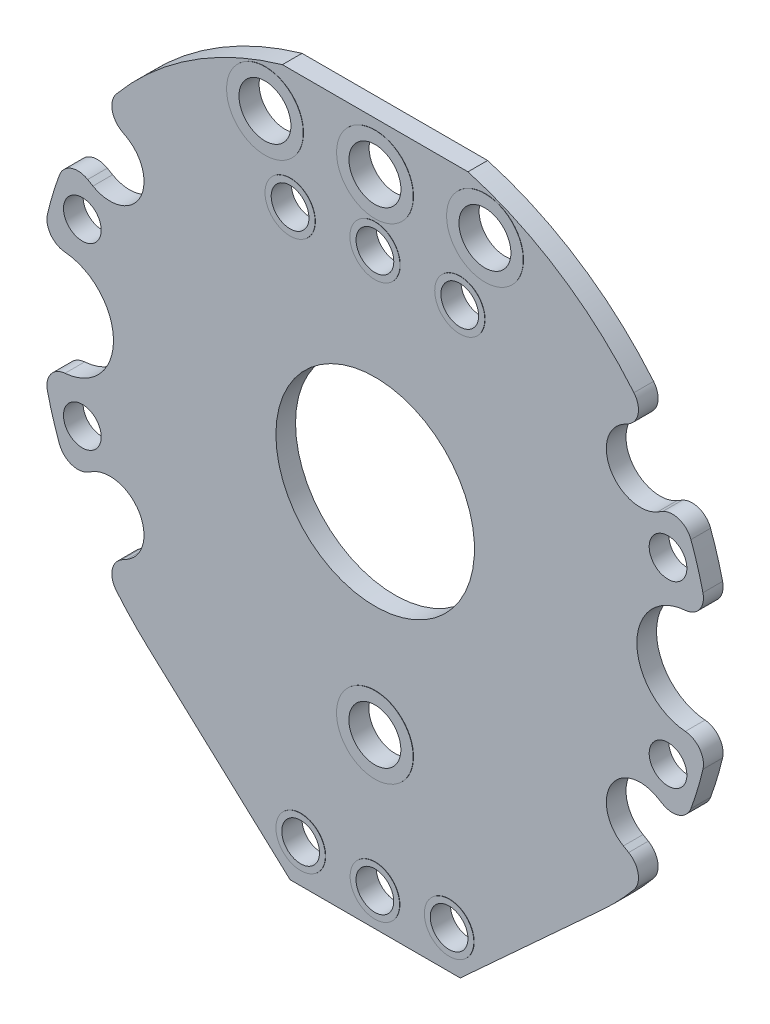
SolidWorks part; units mm, degrees
ref_plane "Front Plane" through (0, 0, 0) normal (0, 0, 1) x (1, 0, 0)
ref_plane "Top Plane" through (0, 0, 0) normal (0, 1, 0) x (1, 0, 0)
ref_plane "Right Plane" through (0, 0, 0) normal (1, 0, 0) x (0, 0, -1)
ref_plane "Plane4" through (0, 0, -0.7937) normal (0, 0, -1) x (-1, 0, 0)
sketch "Sketch1" plane through (0, 0, -0.7937) normal (0, 0, -1) x (-1, 0, 0)
  line L0 (-18.3768, -20.0548) -> (0, -36.8941)
  line L1 (0, -36.8941) -> (18.3768, -20.0548)
  line L2 (7.5, 26.1468) -> (-7.5, 26.1468)
  arc A0 (18.3768, -20.0548) -> (7.5, 26.1468) centre (0, 0) ccw
  arc A1 (-7.5, 26.1468) -> (-18.3768, -20.0548) centre (0, 0) ccw
  dimension "D1" = 15
  dimension "D2" = 26.1468
extrude "Boss-Extrude1" add sketch "Sketch1" against normal blind 1.5875
sketch "Sketch2" plane through (0, 0, 0.7937) normal (0, 0, 1) x (1, 0, 0)
  line L0 (-25.0713, 11.2995) -> (-22.8091, 9.9934)
  line L1 (-20.0591, 14.7566) -> (-22.3213, 16.0626)
  arc A0 (-22.3213, 16.0626) -> (-25.0713, 11.2995) centre (0, 0) ccw
  arc A1 (-22.8091, 9.9934) -> (-20.0591, 14.7566) centre (-21.4341, 12.375) ccw
extrude "Cut-Extrude1" cut sketch "Sketch2" against normal through all
sketch "Sketch3" plane through (0, 0, 0.7937) normal (0, 0, 1) x (1, 0, 0)
  line L0 (22.3213, 16.0626) -> (20.0591, 14.7566)
  line L1 (22.8091, 9.9934) -> (25.0713, 11.2995)
  arc A0 (25.0713, 11.2995) -> (22.3213, 16.0626) centre (0, 0) ccw
  arc A1 (20.0591, 14.7566) -> (22.8091, 9.9934) centre (21.4341, 12.375) ccw
extrude "Cut-Extrude2" cut sketch "Sketch3" against normal through all
sketch "Sketch4" plane through (0, 0, 0.7937) normal (0, 0, 1) x (1, 0, 0)
  line L0 (25.0713, -11.2995) -> (22.8091, -9.9934)
  line L1 (20.0591, -14.7566) -> (22.3213, -16.0626)
  arc A0 (22.3213, -16.0626) -> (25.0713, -11.2995) centre (0, 0) ccw
  arc A1 (22.8091, -9.9934) -> (20.0591, -14.7566) centre (21.4341, -12.375) ccw
extrude "Cut-Extrude3" cut sketch "Sketch4" against normal through all
sketch "Sketch5" plane through (0, 0, 0.7937) normal (0, 0, 1) x (1, 0, 0)
  line L0 (-22.3213, -16.0626) -> (-20.0591, -14.7566)
  line L1 (-22.8091, -9.9934) -> (-25.0713, -11.2995)
  arc A0 (-25.0713, -11.2995) -> (-22.3213, -16.0626) centre (0, 0) ccw
  arc A1 (-20.0591, -14.7566) -> (-22.8091, -9.9934) centre (-21.4341, -12.375) ccw
extrude "Cut-Extrude4" cut sketch "Sketch5" against normal through all
ref_plane "Plane5" through (0, -17, 0) normal (0, -1, 0) x (1, 0, 0)
sketch "Sketch6" plane through (0, -17, 0) normal (0, -1, 0) x (1, 0, 0)
  line L0 (3.0988, 0.8191) -> (0, 0.8192)
  line L1 (0, 0.8192) -> (0, 0.7937)
  line L2 (0, 0.7937) -> (3.0988, 0.7937)
  line L3 (3.0988, 0.7937) -> (3.0988, 0.8191)
  line L4 (0, 0.8192) -> (0, 0.7937) construction
revolve "Revolve1" add sketch "Sketch6" angle 360 about L4
ref_plane "Plane6" through (0, 17.78, 0) normal (0, -1, 0) x (1, 0, 0)
sketch "Sketch7" plane through (0, 17.78, 0) normal (0, -1, 0) x (1, 0, 0)
  line L0 (3.0988, 0.8191) -> (0, 0.8192)
  line L1 (0, 0.8192) -> (0, 0.7937)
  line L2 (0, 0.7937) -> (3.0988, 0.7937)
  line L3 (3.0988, 0.7937) -> (3.0988, 0.8191)
  line L4 (0, 0.8192) -> (0, 0.7937) construction
revolve "Revolve2" [suppressed] add sketch "Sketch7" angle 360 about L4
ref_plane "Plane7" through (0, -27.6013, 0) normal (0, -1, 0) x (1, 0, 0)
sketch "Sketch8" plane through (0, -27.6013, 0) normal (0, -1, 0) x (1, 0, 0)
  line L0 (-5.3958, 0.8191) -> (-7.3958, 0.8192)
  line L1 (-7.3958, 0.8192) -> (-7.3958, 0.7937)
  line L2 (-7.3958, 0.7937) -> (-5.3958, 0.7937)
  line L3 (-5.3958, 0.7937) -> (-5.3958, 0.8191)
  line L4 (-7.3958, 0.8192) -> (-7.3958, 0.7937) construction
revolve "Revolve3" [suppressed] add sketch "Sketch8" angle 360 about L4
sketch "Sketch9" plane through (0, -27.6013, 0) normal (0, -1, 0) x (1, 0, 0)
  line L0 (9.3958, 0.8191) -> (7.3958, 0.8192)
  line L1 (7.3958, 0.8192) -> (7.3958, 0.7937)
  line L2 (7.3958, 0.7937) -> (9.3958, 0.7937)
  line L3 (9.3958, 0.7937) -> (9.3958, 0.8191)
  line L4 (7.3958, 0.8192) -> (7.3958, 0.7937) construction
revolve "Revolve4" [suppressed] add sketch "Sketch9" angle 360 about L4
ref_plane "Plane8" through (0, -28.575, 0) normal (0, -1, 0) x (1, 0, 0)
sketch "Sketch10" plane through (0, -28.575, 0) normal (0, -1, 0) x (1, 0, 0)
  line L0 (2, 0.8191) -> (0, 0.8192)
  line L1 (0, 0.8192) -> (0, 0.7937)
  line L2 (0, 0.7937) -> (2, 0.7937)
  line L3 (2, 0.7937) -> (2, 0.8191)
  line L4 (0, 0.8192) -> (0, 0.7937) construction
revolve "Revolve5" add sketch "Sketch10" angle 360 about L4
ref_plane "Plane9" through (0, 16.4194, 0) normal (0, -1, 0) x (1, 0, 0)
sketch "Sketch11" plane through (0, 16.4194, 0) normal (0, -1, 0) x (1, 0, 0)
  line L0 (-3.7225, 0.8191) -> (-6.8213, 0.8192)
  line L1 (-6.8213, 0.8192) -> (-6.8213, 0.7937)
  line L2 (-6.8213, 0.7937) -> (-3.7225, 0.7937)
  line L3 (-3.7225, 0.7937) -> (-3.7225, 0.8191)
  line L4 (-6.8213, 0.8192) -> (-6.8213, 0.7937) construction
revolve "Revolve6" [suppressed] add sketch "Sketch11" angle 360 about L4
sketch "Sketch12" plane through (0, 16.4194, 0) normal (0, -1, 0) x (1, 0, 0)
  line L0 (9.9201, 0.8191) -> (6.8213, 0.8192)
  line L1 (6.8213, 0.8192) -> (6.8213, 0.7937)
  line L2 (6.8213, 0.7937) -> (9.9201, 0.7937)
  line L3 (9.9201, 0.7937) -> (9.9201, 0.8191)
  line L4 (6.8213, 0.8192) -> (6.8213, 0.7937) construction
revolve "Revolve7" [suppressed] add sketch "Sketch12" angle 360 about L4
sketch "Sketch15" plane through (0, -27.6013, 0) normal (0, -1, 0) x (1, 0, 0)
  line L0 (-5.3958, -0.7937) -> (-7.3958, -0.7937)
  line L1 (-7.3958, -0.7937) -> (-7.3958, -0.8192)
  line L2 (-7.3958, -0.8192) -> (-5.3958, -0.8191)
  line L3 (-5.3958, -0.8191) -> (-5.3958, -0.7937)
  line L4 (-7.3958, -0.7937) -> (-7.3958, -0.8192) construction
revolve "Revolve10" [suppressed] add sketch "Sketch15" angle 360 about L4
sketch "Sketch16" plane through (0, -27.6013, 0) normal (0, -1, 0) x (1, 0, 0)
  line L0 (9.3958, -0.7937) -> (7.3958, -0.7937)
  line L1 (7.3958, -0.7937) -> (7.3958, -0.8192)
  line L2 (7.3958, -0.8192) -> (9.3958, -0.8191)
  line L3 (9.3958, -0.8191) -> (9.3958, -0.7937)
  line L4 (7.3958, -0.7937) -> (7.3958, -0.8192) construction
revolve "Revolve11" [suppressed] add sketch "Sketch16" angle 360 about L4
hole_wizard "M14 Clearance Hole1" positions "Sketch21" profile "Sketch20" hole size "M14" standard "ANSI Metric"
sketch "Sketch21" plane through (0, 0, -0.7937) normal (0, 0, -1) x (-1, 0, 0)
  point P0 (0, 0)
sketch "Sketch20" plane through (0, 0, -0.7937) normal (1, 0, 0) x (0, 1, 0)
  line L0 (0, 0) -> (0, 1.6129)
  line L1 (0, 1.6129) -> (8.025, 1.6129)
  line L2 (8.025, 1.6129) -> (8.025, 0)
  line L5 (8.025, 0) -> (0, 0)
  line L11 (0, -6.35) -> (0, 107.95) construction
  dimension "Thru Hole Dia." = 16.05
  dimension "Thru Hole Depth" = 1.6129
hole_wizard "Ø8.5 (8.5) Diameter Hole1" positions "Sketch23" profile "Sketch22" hole size "Ø8.5" standard "ANSI Metric"
sketch "Sketch23" plane through (0, 0, 0.7937) normal (0, 0, 1) x (1, 0, 0)
  point P0 (-25.4, 0)
sketch "Sketch22" plane through (-25.4, 0, 0.7937) normal (1, 0, 0) x (0, -1, 0)
  line L0 (0, 0) -> (0, 1.5875)
  line L1 (0, 1.5875) -> (4.25, 1.5875)
  line L2 (4.25, 1.5875) -> (4.25, 0)
  line L5 (4.25, 0) -> (0, 0)
  line L11 (0, -6.35) -> (0, 107.95) construction
  dimension "Thru Hole Dia." = 8.5
  dimension "Thru Hole Depth" = 1.5875
hole_wizard "Ø8.5 (8.5) Diameter Hole2" positions "Sketch25" profile "Sketch24" hole size "Ø8.5" standard "ANSI Metric"
sketch "Sketch25" plane through (0, 0, -0.7937) normal (0, 0, -1) x (-1, 0, 0)
  point P0 (-25.4, 0)
sketch "Sketch24" plane through (25.4, 0, -0.7937) normal (1, 0, 0) x (0, 1, 0)
  line L0 (0, 0) -> (0, 1.6129)
  line L1 (0, 1.6129) -> (4.25, 1.6129)
  line L2 (4.25, 1.6129) -> (4.25, 0)
  line L5 (4.25, 0) -> (0, 0)
  line L11 (0, -6.35) -> (0, 107.95) construction
  dimension "Thru Hole Dia." = 8.5
  dimension "Thru Hole Depth" = 1.6129
sketch "Sketch17" plane through (0, -28.575, 0) normal (0, -1, 0) x (1, 0, 0)
  line L0 (2, -0.7937) -> (0, -0.7937)
  line L1 (0, -0.7937) -> (0, -0.8192)
  line L2 (0, -0.8192) -> (2, -0.8191)
  line L3 (2, -0.8191) -> (2, -0.7937)
  line L4 (0, -0.7937) -> (0, -0.8192) construction
revolve "Revolve12" add sketch "Sketch17" angle 360 about L4
hole_wizard "M2.5 Clearance Hole1" positions "Sketch27" profile "Sketch26" hole size "M2.5" standard "ANSI Metric" end condition through all
sketch "Sketch27" plane through (0, 0, -0.8191) normal (0, 0, -1) x (-1, 0, 0)
  point P0 (0, -27.9)
  point P1 (-6, -27.5)
  point P2 (6, -27.5)
  point P3 (23.6685, 7.2362)
  point P4 (23.6685, -7.2362)
  point P5 (-23.6685, -7.2362)
  point P6 (-23.6685, 7.2362)
  dimension "D1" = 27.5
  dimension "D2" = 27.9
  dimension "D3" = 6
  dimension "D4" = 6
sketch "Sketch26" plane through (0, -27.9, -0.8191) normal (1, 0, 0) x (0, 1, 0)
  line L0 (0, 0) -> (0, 1.6383)
  line L1 (0, 1.6383) -> (1.524, 1.6383)
  line L2 (1.524, 1.6383) -> (1.524, 0)
  line L5 (1.524, 0) -> (0, 0)
  line L11 (0, -6.35) -> (0, 107.95) construction
  dimension "Thru Hole Dia." = 3.048
  dimension "Thru Hole Depth" = 1.6383
hole_wizard "M3.5 Clearance Hole1" positions "Sketch29" profile "Sketch28" hole size "M3.5" standard "ANSI Metric" end condition through all
sketch "Sketch29" plane through (0, 0, -0.7937) normal (0, 0, -1) x (-1, 0, 0)
  point P0 (-8.89, 22.225)
  point P1 (8.89, 22.225)
  point P2 (0, 22.225)
  point P3 (0, -17)
sketch "Sketch28" plane through (8.89, 22.225, -0.7937) normal (1, 0, 0) x (0, 1, 0)
  line L0 (0, 0) -> (0, 1.6129)
  line L1 (0, 1.6129) -> (2.1, 1.6129)
  line L2 (2.1, 1.6129) -> (2.1, 0)
  line L5 (2.1, 0) -> (0, 0)
  line L11 (0, -6.35) -> (0, 107.95) construction
  dimension "Thru Hole Dia." = 4.2
  dimension "Thru Hole Depth" = 1.6129
sketch "Sketch13" plane through (0, -17, 0) normal (0, -1, 0) x (1, 0, 0)
  line L0 (3.0988, -0.7937) -> (0, -0.7937)
  line L1 (0, -0.7937) -> (0, -0.8192)
  line L2 (0, -0.8192) -> (3.0988, -0.8191)
  line L3 (3.0988, -0.8191) -> (3.0988, -0.7937)
  line L4 (0, -0.7937) -> (0, -0.8192) construction
revolve "Revolve8" [suppressed] add sketch "Sketch13" angle 360 about L4
sketch "Sketch18" plane through (0, 16.4194, 0) normal (0, -1, 0) x (1, 0, 0)
  line L0 (-3.7225, -0.7937) -> (-6.8213, -0.7937)
  line L1 (-6.8213, -0.7937) -> (-6.8213, -0.8192)
  line L2 (-6.8213, -0.8192) -> (-3.7225, -0.8191)
  line L3 (-3.7225, -0.8191) -> (-3.7225, -0.7937)
  line L4 (-6.8213, -0.7937) -> (-6.8213, -0.8192) construction
revolve "Revolve13" [suppressed] add sketch "Sketch18" angle 360 about L4
sketch "Sketch14" plane through (0, 17.78, 0) normal (0, -1, 0) x (1, 0, 0)
  line L0 (3.0988, -0.7937) -> (0, -0.7937)
  line L1 (0, -0.7937) -> (0, -0.8192)
  line L2 (0, -0.8192) -> (3.0988, -0.8191)
  line L3 (3.0988, -0.8191) -> (3.0988, -0.7937)
  line L4 (0, -0.7937) -> (0, -0.8192) construction
revolve "Revolve9" [suppressed] add sketch "Sketch14" angle 360 about L4
chamfer "Chamfer1" distance 9.3243 angle 42.5 1 edges at (0, -36.8941, 0)
fillet "Fillet1" radius 1.5875 12 edges at (-26.9095, 3.9729, 0) (-26.9095, -3.9729, 0) (-24.8112, -11.1493, 0) (-22.0612, -15.9125, 0) (-22.0612, 15.9125, 0) (-24.8112, 11.1493, 0) (22.0612, 15.9125, 0) (24.8112, 11.1493, 0) (26.9095, -3.9729, 0) (26.9095, 3.9729, 0) (24.8112, -11.1493, 0) (22.0612, -15.9125, 0)
sketch "Sketch30" plane through (0, 0, 0.7937) normal (0, 0, 1) x (1, 0, 0)
  circle A0 centre (-8.89, 22.225) radius 3.1
  circle A1 centre (0, 22.225) radius 3.1
  circle A2 centre (8.89, 22.225) radius 3.1
  circle A3 centre (8.89, 22.225) radius 2.1 construction
  circle A4 centre (0, 22.225) radius 2.1 construction
  circle A5 centre (-8.89, 22.225) radius 2.1 construction
  circle A6 centre (8.89, 22.225) radius 2.1
  circle A7 centre (0, 22.225) radius 2.1
  circle A8 centre (-8.89, 22.225) radius 2.1
  dimension "D1" = 6.2
extrude "Boss-Extrude2" add sketch "Sketch30" along normal blind 0.02
mirror "Mirror1" about plane through (0, 0, 0) normal (0, 0, 1) of "Boss-Extrude2"
sketch "Sketch31" plane through (0, 0, 0.7937) normal (0, 0, 1) x (1, 0, 0)
  circle A0 centre (-6.858, 16.51) radius 2.025
  circle A1 centre (0, 16.8813) radius 2.025
  circle A2 centre (6.858, 16.51) radius 2.025
  circle A3 centre (0, 16.8813) radius 1.525
  circle A4 centre (-6.858, 16.51) radius 1.525
  circle A5 centre (6.858, 16.51) radius 1.525
  dimension "D1" = 3.05
  dimension "D2" = 0.5
extrude "Boss-Extrude3" add sketch "Sketch31" along normal blind 0.0207
sketch "Sketch32" plane through (0, 0, 0.7937) normal (0, 0, 1) x (1, 0, 0)
  circle A1 centre (6.858, 16.51) radius 1.525 construction
  circle A2 centre (0, 16.8813) radius 1.525 construction
  circle A3 centre (-6.858, 16.51) radius 1.525 construction
  circle A4 centre (6.858, 16.51) radius 1.525
  circle A5 centre (0, 16.8813) radius 1.525
  circle A6 centre (-6.858, 16.51) radius 1.525
extrude "Cut-Extrude6" cut sketch "Sketch32" against normal through all
mirror "Mirror2" about plane through (0, 0, 0) normal (0, 0, 1) of "Boss-Extrude3"
sketch "Sketch33" plane through (0, 0, 0.7937) normal (0, 0, 1) x (1, 0, 0)
  line L1 (-7.3512, -28.9746) -> (-7.1679, -29.1425) construction
  line L2 (-6.8746, -30.5947) -> (-18.3768, -20.0548) construction
  circle A0 centre (-6, -27.5) radius 2
  circle A1 centre (6, -27.5) radius 2
  circle A2 centre (0, -28.575) radius 2 construction
  circle A3 centre (6, -27.5) radius 1.524 construction
  circle A4 centre (-6, -27.5) radius 1.524 construction
  circle A5 centre (6, -27.5) radius 1.524
  circle A6 centre (-6, -27.5) radius 1.524
extrude "Boss-Extrude4" add sketch "Sketch33" along normal up to surface (0.0254 mm away) up to face at (-2.1, -17, 0.8191)
sketch "Sketch34" plane through (0, 0, 0.8191) normal (0, 0, -1) x (-1, 0, 0)
  circle A0 centre (0, -28.575) radius 2
  circle A1 centre (0, -28.575) radius 2 construction
extrude "Cut-Extrude8" cut sketch "Sketch34" along normal up to surface (0.0254 mm away) up to face at (-8, -27.5, 0.7938)
sketch "Sketch36" plane through (0, 0, -0.8191) normal (0, 0, -1) x (-1, 0, 0)
  circle A2 centre (0, -28.575) radius 2
  circle A3 centre (0, -28.575) radius 2 construction
extrude "Cut-Extrude9" cut sketch "Sketch36" against normal up to surface (0.0254 mm away) up to face at (4.833, 16.51, -0.7937)
sketch "Sketch37" plane through (0, 0, 0.7937) normal (0, 0, 1) x (1, 0, 0)
  circle A0 centre (0, -27.9) radius 2
  circle A1 centre (-6, -27.5) radius 2 construction
  circle A2 centre (0, -27.9) radius 1.524 construction
  circle A3 centre (0, -27.9) radius 1.524
extrude "Boss-Extrude5" add sketch "Sketch37" along normal up to surface (0.0254 mm away) up to face at (-4.476, -27.5, 0.8191)
sketch "Sketch38" plane through (0, 0, -0.7937) normal (0, 0, -1) x (-1, 0, 0)
  circle A0 centre (0, -27.9) radius 2
  circle A1 centre (6, -27.5) radius 2
  circle A2 centre (-6, -27.5) radius 2
  circle A3 centre (0, -27.9) radius 2 construction
  circle A4 centre (6, -27.5) radius 1.524 construction
  circle A5 centre (0, -27.9) radius 1.524 construction
  circle A6 centre (-6, -27.5) radius 1.524 construction
  circle A7 centre (6, -27.5) radius 1.524
  circle A8 centre (0, -27.9) radius 1.524
  circle A9 centre (-6, -27.5) radius 1.524
extrude "Boss-Extrude6" add sketch "Sketch38" along normal up to surface (0.02 mm away) up to face at (10.99, 22.225, -0.8137)
sketch "Sketch39" [suppressed] plane through (0, 0, -0.7937) normal (0, 0, -1) x (-1, 0, 0)
  circle A0 centre (0, -17) radius 3.0988
  circle A1 centre (0, -17) radius 3.0988 construction
  circle A2 centre (0, -17) radius 2.1 construction
  circle A3 centre (0, -17) radius 2.1
extrude "Boss-Extrude7" [suppressed] add sketch "Sketch39" along normal blind 0.0207
